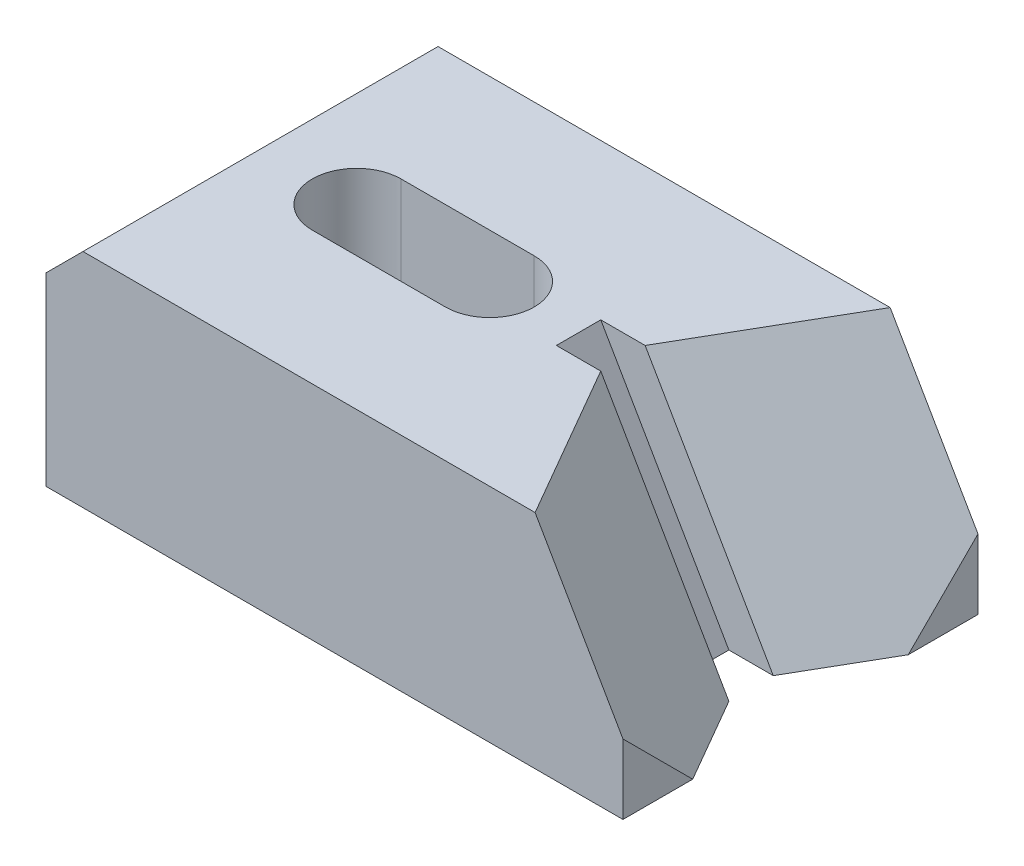
SolidWorks part; units mm, degrees
ref_plane "Front Plane" through (0, 0, 0) normal (0, 0, 1) x (1, 0, 0)
ref_plane "Top Plane" through (0, 0, 0) normal (0, 1, 0) x (1, 0, 0)
ref_plane "Right Plane" through (0, 0, 0) normal (1, 0, 0) x (0, 0, -1)
sketch "Sketch1" plane through (0, 0, 0) normal (0, 1, 0) x (1, 0, 0)
  line L1 (0, 24) -> (78, 24)
  line L2 (0, 24) -> (0, -24)
  line L3 (0, -24) -> (78, -24)
  line L4 (78, 24) -> (78, -24)
  point P4 (0, 0)
  dimension "D1" = 78
  dimension "D2" = 48
extrude "Boss-Extrude1" add sketch "Sketch1" along normal blind 30
chamfer "Chamfer1" distance 5 angle 45 1 edges at (0, 30, 0)
sketch "Sketch2" plane through (0, 30, 0) normal (0, 1, 0) x (1, 0, 0)
  line L0 (18, 0) -> (36, 0) construction
  line L1 (18, 6) -> (36, 6)
  line L2 (18, -6) -> (36, -6)
  line L3 (0, -24) -> (0, 24) construction
  arc A0 (18, 6) -> (18, -6) centre (18, 0) ccw
  arc A1 (36, -6) -> (36, 6) centre (36, 0) ccw
  point P3 (27, 0)
  dimension "D1" = 18
  dimension "D2" = 18
  dimension "D3" = 12
extrude "Cut-Extrude1" cut sketch "Sketch2" against normal through all
sketch "Sketch3" plane through (0, 30, 0) normal (0, 1, 0) x (1, 0, 0)
  line L0 (78, 24) -> (66.1244, 24)
  line L1 (78, 24) -> (5, 24) construction
  line L2 (66.1244, 24) -> (54, 3)
  line L3 (54, 3) -> (48, 3)
  line L4 (48, 3) -> (48, -3)
  line L5 (0, 0) -> (89.3085, 0) construction
  line L6 (0, -24) -> (0, 24) construction
  line L7 (78, 24) -> (78, -24)
  line L8 (54, -3) -> (48, -3)
  line L9 (66.1244, -24) -> (54, -3)
  line L10 (78, -24) -> (66.1244, -24)
  point P14 (78, 0)
  point P15 (48, 0)
  dimension "D1" = 6
  dimension "D2" = 6
  dimension "D3" = 120
  dimension "D4" = 48
sketch "Sketch4" plane through (0, 0, 0) normal (0, 0, 1) x (1, 0, 0)
  line L0 (48, 30) -> (65.3205, 0)
  line L1 (0, 0) -> (78, 0) construction
  line L2 (66.1244, 30) -> (54, 30) construction
  dimension "D1" = 60
extrude "Cut-Extrude2" cut sketch "Sketch3" along direction (0.5, -0.866, 0) on the side against the normal through all
